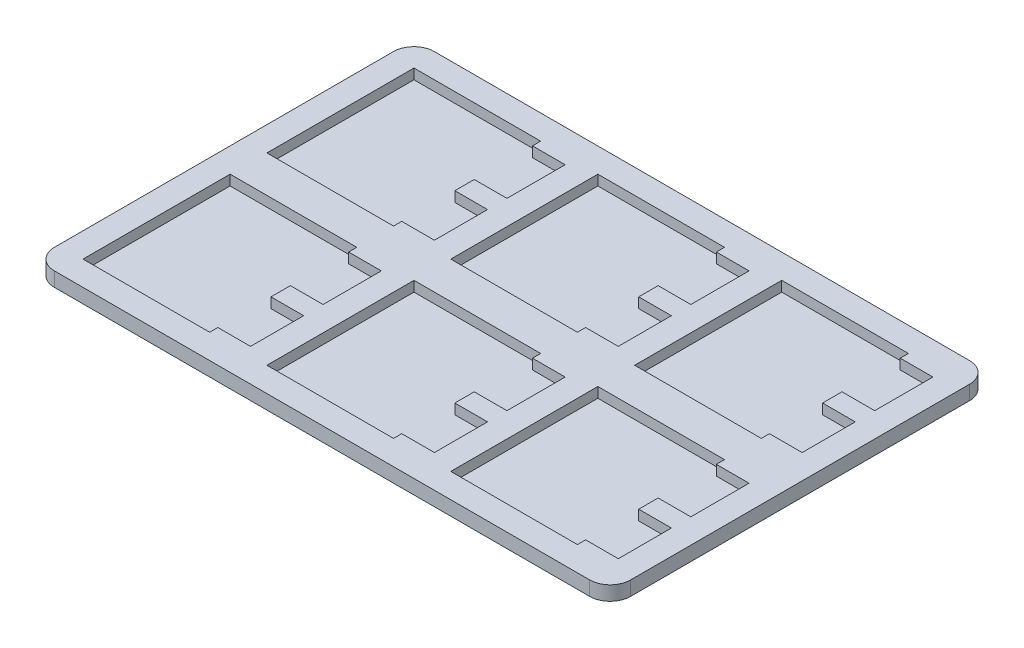
SolidWorks part; units mm, degrees
ref_plane "Front Plane" through (0, 0, 0) normal (0, 0, 1) x (1, 0, 0)
ref_plane "Top Plane" through (0, 0, 0) normal (0, 1, 0) x (1, 0, 0)
ref_plane "Right Plane" through (0, 0, 0) normal (1, 0, 0) x (0, 0, -1)
sketch "Sketch2" plane through (0, 0, 0) normal (0, 1, 0) x (1, 0, 0)
  line L1 (10, 0) -> (272, 0)
  line L2 (0, 10) -> (0, 175.95)
  line L3 (10, 185.95) -> (272, 185.95)
  line L4 (282, 10) -> (282, 175.95)
  arc A0 (272, 185.95) -> (282, 175.95) centre (272, 175.95) cw
  arc A1 (272, 0) -> (282, 10) centre (272, 10) ccw
  arc A2 (10, 0) -> (0, 10) centre (10, 10) cw
  arc A3 (0, 175.95) -> (10, 185.95) centre (10, 175.95) cw
  point P11 (0, 0)
  dimension "D1" = 10
  dimension "D2" = 165.95
  dimension "D3" = 262
extrude "Boss-Extrude1" add sketch "Sketch2" along normal blind 7
sketch "Sketch3" plane through (0, 7, 0) normal (0, 1, 0) x (1, 0, 0)
  line L0 (74, 16) -> (90, 16)
  line L1 (12, 12) -> (74, 12)
  line L2 (12, 12) -> (12, 84)
  line L3 (12, 84) -> (74, 84)
  line L4 (74, 12) -> (74, 16)
  line L5 (90, 16) -> (90, 42)
  line L6 (90, 42) -> (74, 42)
  line L7 (74, 42) -> (74, 51.5)
  line L8 (74, 80) -> (90, 80)
  line L9 (90, 80) -> (90, 51.5)
  line L10 (90, 51.5) -> (74, 51.5)
  line L11 (74, 80) -> (74, 84)
  line L12 (0, 175.95) -> (0, 10) construction
  line L13 (10, 0) -> (272, 0) construction
  line L14 (96, 0) -> (96, 190.7769) construction
  line L15 (180, 42) -> (164, 42)
  line L16 (164, 42) -> (164, 51.5)
  line L17 (180, 51.5) -> (164, 51.5)
  line L18 (180, 80) -> (180, 51.5)
  line L19 (164, 80) -> (180, 80)
  line L20 (164, 80) -> (164, 84)
  line L21 (102, 84) -> (164, 84)
  line L22 (102, 12) -> (102, 84)
  line L23 (102, 12) -> (164, 12)
  line L24 (164, 12) -> (164, 16)
  line L25 (164, 16) -> (180, 16)
  line L26 (180, 16) -> (180, 42)
  line L27 (270, 42) -> (254, 42)
  line L28 (254, 42) -> (254, 51.5)
  line L29 (270, 51.5) -> (254, 51.5)
  line L30 (270, 80) -> (270, 51.5)
  line L31 (254, 80) -> (270, 80)
  line L32 (254, 80) -> (254, 84)
  line L33 (192, 84) -> (254, 84)
  line L34 (192, 12) -> (192, 84)
  line L35 (192, 12) -> (254, 12)
  line L36 (254, 12) -> (254, 16)
  line L37 (254, 16) -> (270, 16)
  line L38 (270, 16) -> (270, 42)
  line L39 (180, 132) -> (164, 132)
  line L40 (164, 132) -> (164, 141.5)
  line L41 (180, 141.5) -> (164, 141.5)
  line L42 (180, 170) -> (180, 141.5)
  line L43 (164, 170) -> (180, 170)
  line L44 (164, 170) -> (164, 174)
  line L45 (102, 174) -> (164, 174)
  line L46 (102, 102) -> (102, 174)
  line L47 (102, 102) -> (164, 102)
  line L48 (164, 102) -> (164, 106)
  line L49 (164, 106) -> (180, 106)
  line L50 (180, 106) -> (180, 132)
  line L51 (270, 132) -> (254, 132)
  line L52 (254, 132) -> (254, 141.5)
  line L53 (270, 141.5) -> (254, 141.5)
  line L54 (270, 170) -> (270, 141.5)
  line L55 (254, 170) -> (270, 170)
  line L56 (254, 170) -> (254, 174)
  line L57 (192, 174) -> (254, 174)
  line L58 (192, 102) -> (192, 174)
  line L59 (192, 102) -> (254, 102)
  line L60 (254, 102) -> (254, 106)
  line L61 (254, 106) -> (270, 106)
  line L62 (270, 106) -> (270, 132)
  line L63 (90, 132) -> (74, 132)
  line L64 (74, 132) -> (74, 141.5)
  line L65 (90, 141.5) -> (74, 141.5)
  line L66 (90, 170) -> (90, 141.5)
  line L67 (74, 170) -> (90, 170)
  line L68 (74, 170) -> (74, 174)
  line L69 (12, 174) -> (74, 174)
  line L70 (12, 102) -> (12, 174)
  line L71 (12, 102) -> (74, 102)
  line L72 (74, 102) -> (74, 106)
  line L73 (74, 106) -> (90, 106)
  line L74 (90, 106) -> (90, 132)
  dimension "D1" = 72
  dimension "D2" = 62
  dimension "D3" = 4
  dimension "D4" = 9.5
  dimension "D5" = 16
  dimension "D6" = 4
  dimension "D7" = 6
  dimension "D8" = 16
  dimension "D9" = 12
  dimension "D10" = 12
  dimension "D11" = 3
  dimension "D12" = 2
extrude "Cut-Extrude1" cut sketch "Sketch3" against normal blind 5
